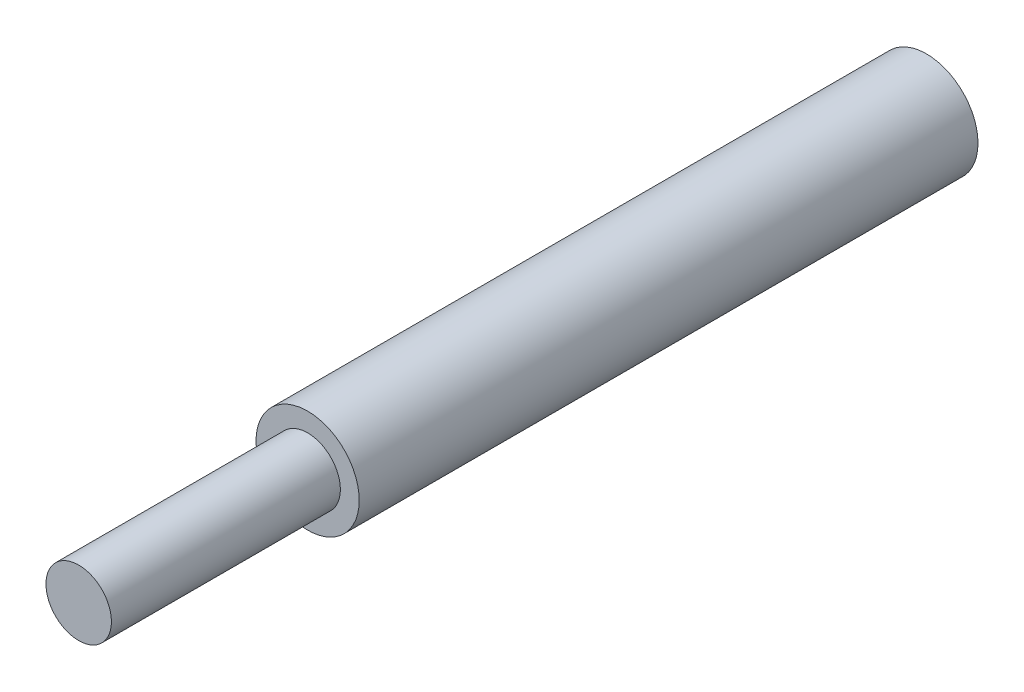
SolidWorks part; units mm, degrees
material "AISI 4340 Steel, normalized"
ref_plane "Front Plane" through (0, 0, 0) normal (0, 0, 1) x (1, 0, 0)
ref_plane "Top Plane" through (0, 0, 0) normal (0, 1, 0) x (1, 0, 0)
ref_plane "Right Plane" through (0, 0, 0) normal (1, 0, 0) x (0, 0, -1)
sketch "Sketch1" plane through (0, 0, 0) normal (0, 0, 1) x (1, 0, 0)
  circle A0 centre (0, 0) radius 5
extrude "Rod_At_Midstroke_30mm" add sketch "Sketch1" along normal blind 60 from offset 44.5
sketch "Sketch2" plane through (0, 0, 0) normal (0, 0, 1) x (1, 0, 0)
  circle A0 centre (0, 0) radius 3.175
extrude "Quarter20_Thread_Major_Envelope" add sketch "Sketch2" along normal blind 22.2 from offset 104.5
